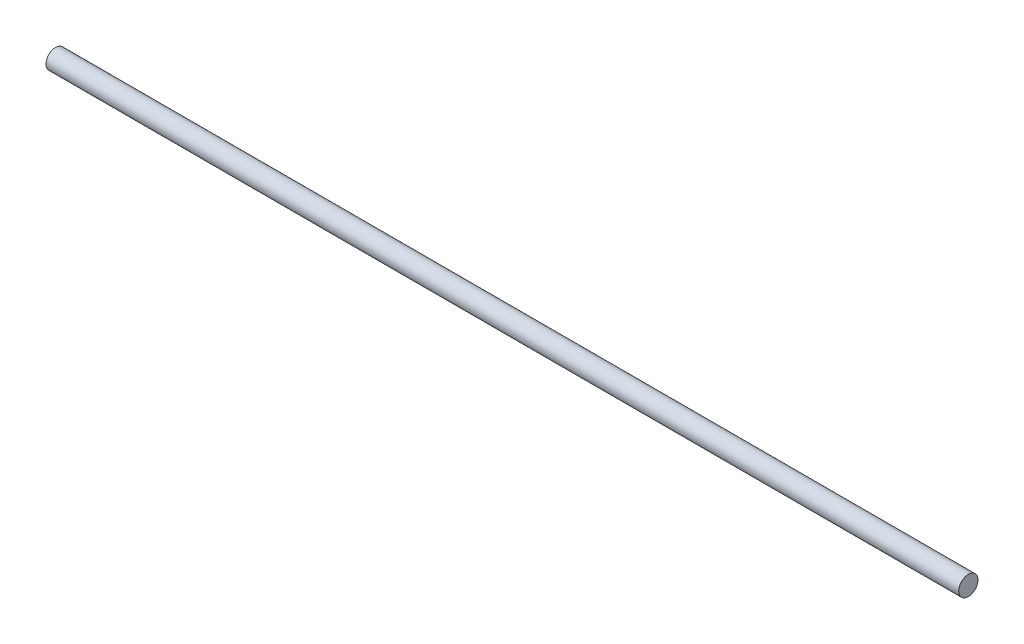
SolidWorks part; units mm, degrees
material "A-Glass Fiber"
ref_plane "Front Plane" through (0, 0, 0) normal (0, 0, 1) x (1, 0, 0)
ref_plane "Top Plane" through (0, 0, 0) normal (0, 1, 0) x (1, 0, 0)
ref_plane "Right Plane" through (0, 0, 0) normal (1, 0, 0) x (0, 0, -1)
sketch "Sketch1" plane through (0, 0, 0) normal (1, 0, 0) x (0, 0, -1)
  circle A0 centre (0, 0) radius 6.35
  dimension "D1" = 12.7
extrude "Boss-Extrude1" add sketch "Sketch1" along normal mid plane 600
